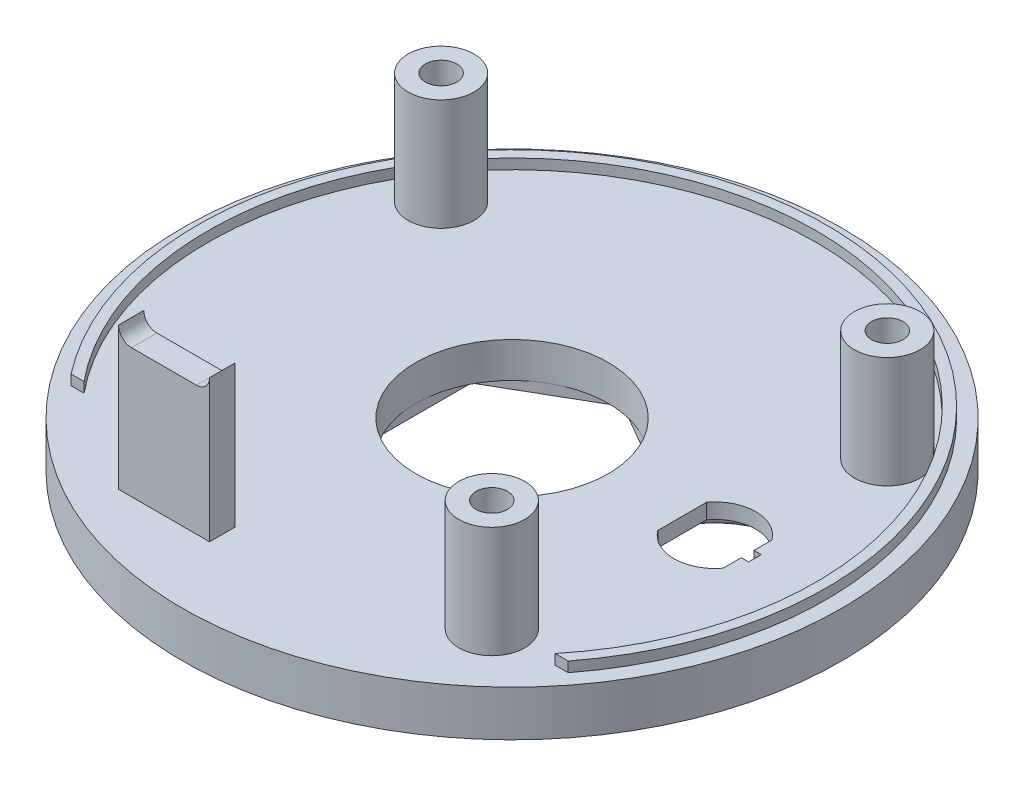
SolidWorks part; units mm, degrees
ref_plane "Front Plane" through (0, 0, 0) normal (0, 0, 1) x (1, 0, 0)
ref_plane "Top Plane" through (0, 0, 0) normal (0, 1, 0) x (1, 0, 0)
ref_plane "Right Plane" through (0, 0, 0) normal (1, 0, 0) x (0, 0, -1)
sketch "Sketch1" plane through (0, 0, 0) normal (0, 1, 0) x (1, 0, 0)
  circle A0 centre (0, 0) radius 32.5
  dimension "D1" = 65
extrude "Boss-Extrude1" add sketch "Sketch1" along normal blind 21
shell "Shell1" thickness 2.5
sketch "Sketch4" plane through (0, 21, 0) normal (0, 1, 0) x (1, 0, 0)
  line L0 (-19.2835, -22.9814) -> (19.2835, -22.9814)
  line L1 (-19.2835, -22.9814) -> (-22.9805, -22.9814)
  line L2 (19.2835, -22.9814) -> (22.9805, -22.9814)
  circle A0 centre (0, 0) radius 30 construction
  circle A1 centre (0, 0) radius 32.5 construction
  arc A2 (-22.9805, -22.9814) -> (22.9805, -22.9814) centre (0, 0) ccw
  dimension "D1" = 38.567
extrude "Cut-Extrude2" cut sketch "Sketch4" against normal up to surface (18.5 mm away) up to face at (0, 2.5, 30)
sketch "Sketch5" plane through (0, 2.5, 0) normal (0, 1, 0) x (1, 0, 0)
  line L4 (-22.9805, -22.9814) -> (22.9805, -22.9814)
  line L5 (-20.1729, -25.4814) -> (20.1729, -25.4814)
  arc A1 (-22.9805, -22.9814) -> (-20.1729, -25.4814) centre (0, 0) ccw
  arc A2 (-22.9805, -22.9814) -> (22.9805, -22.9814) centre (0, 0) ccw construction
  arc A3 (20.1729, -25.4814) -> (22.9805, -22.9814) centre (0, 0) ccw
  dimension "D1" = 2.5
extrude "Boss-Extrude2" add sketch "Sketch5" along normal through all
sketch "Sketch9" plane through (0, 2.5, 0) normal (0, 1, 0) x (1, 0, 0)
  circle A0 centre (-22, 15) radius 3.25
  circle A1 centre (22, 15) radius 3.25
  circle A2 centre (17, -19) radius 3.25
  dimension "D6" = 6.5
  dimension "D1" = 22
  dimension "D2" = 15
  dimension "D3" = 22
  dimension "D4" = 19
  dimension "D5" = 17
extrude "Boss-Extrude3" add sketch "Sketch9" along normal blind 10.97
sketch "Sketch10" plane through (0, 21, 0) normal (0, 1, 0) x (1, 0, 0)
  line L0 (-20.1729, -25.4814) -> (-13.33, -25.4814)
  line L1 (-20.1729, -25.4814) -> (20.1729, -25.4814) construction
  line L2 (-13.33, -25.4814) -> (-13.33, -22.9814)
  line L3 (19.2835, -22.9814) -> (-19.2835, -22.9814) construction
  line L4 (-13.33, -22.9814) -> (-19.2835, -22.9814)
  line L5 (20.1729, -25.4814) -> (-4.35, -25.4814)
  line L6 (-4.35, -25.4814) -> (-4.35, -22.9814)
  line L7 (-4.35, -22.9814) -> (19.2835, -22.9814)
  arc A0 (-20.1729, -25.4814) -> (20.1729, -25.4814) centre (0, 0) cw
  arc A1 (20.1729, -25.4814) -> (-20.1729, -25.4814) centre (0, 0) ccw construction
  arc A2 (-19.2835, -22.9814) -> (19.2835, -22.9814) centre (0, 0) cw
  arc A3 (19.2835, -22.9814) -> (-19.2835, -22.9814) centre (0, 0) ccw construction
  dimension "D1" = 8.98
  dimension "D2" = 5.9535
extrude "Cut-Extrude4" cut sketch "Sketch10" against normal up to surface (18.5 mm away)
sketch "Sketch11" plane through (0, 0, 25.4814) normal (0, 0, 1) x (1, 0, 0)
  line L0 (-12.04, 16.52) -> (-5.64, 16.52) construction
  line L1 (-13.33, 21) -> (-4.35, 21) construction
  line L3 (-12.04, 15.23) -> (-5.64, 15.23)
  line L4 (-13.33, 2.5) -> (-4.35, 2.5) construction
  line L5 (-4.35, 2.5) -> (-4.35, 21) construction
  line L7 (-13.33, 16.52) -> (-13.33, 21)
  line L8 (-13.33, 21) -> (-4.35, 21)
  line L9 (-4.35, 16.52) -> (-4.35, 21)
  line L10 (-13.33, 2.5) -> (-13.33, 21) construction
  arc A0 (-13.33, 16.52) -> (-12.04, 15.23) centre (-12.04, 16.52) ccw
  arc A1 (-5.64, 15.23) -> (-4.35, 16.52) centre (-5.64, 16.52) ccw
  point P4 (-8.84, 14.2241)
  dimension "D1" = 1.29
  dimension "D2" = 12.73
extrude "Cut-Extrude5" cut sketch "Sketch11" against normal through all
sketch "Sketch12" plane through (0, 2.5, 0) normal (0, 1, 0) x (1, 0, 0)
  line L0 (-24.5093, -18.9814) -> (-23.2315, -18.9814)
  line L1 (23.2315, -18.9814) -> (24.5093, -18.9814)
  line L2 (-4.35, -22.9814) -> (-13.33, -22.9814) construction
  arc A0 (-23.2315, -18.9814) -> (23.2315, -18.9814) centre (0, 0) cw
  arc A1 (-24.5093, -18.9814) -> (24.5093, -18.9814) centre (0, 0) cw
  dimension "D1" = 1
  dimension "D3" = 31
  dimension "D2" = 4
extrude "Boss-Extrude4" add sketch "Sketch12" along normal blind 1
sketch "Sketch15" plane through (0, 0, 0) normal (0, -1, 0) x (1, 0, 0)
  circle A0 centre (0, 0) radius 32.5
  circle A1 centre (0, 0) radius 32.5 construction
extrude "Boss-Extrude5" add sketch "Sketch15" along normal blind 2
sketch "Sketch13" plane through (0, 2.5, 0) normal (0, 1, 0) x (1, 0, 0)
  line L0 (16.775, 2.4083) -> (16.775, -2.4083)
  line L3 (23.225, 2.4083) -> (23.225, 0.625)
  line L4 (23.225, -0.625) -> (23.225, -2.4083)
  line L5 (23.225, 0.625) -> (23.95, 0.625)
  line L7 (23.225, -0.625) -> (23.95, -0.625)
  line L8 (23.95, 0.625) -> (23.95, -0.625)
  line L9 (16.775, 2.4083) -> (23.225, 2.4083) construction
  line L10 (16.775, -2.4083) -> (23.225, -2.4083) construction
  arc A2 (16.775, -2.4083) -> (23.225, -2.4083) centre (20, 0) ccw
  arc A3 (23.225, 2.4083) -> (16.775, 2.4083) centre (20, 0) ccw
  circle A4 centre (0, 0) radius 9.5
  point P12 (23.95, 0)
  dimension "D1" = 8.05
  dimension "D4" = 19
  dimension "D2" = 20
  dimension "D3" = 6.45
  dimension "D5" = 3.95
  dimension "D6" = 1.25
extrude "Cut-Extrude6" cut sketch "Sketch13" against normal through all
sketch "Sketch17" plane through (0, -2, 0) normal (0, -1, 0) x (1, 0, 0)
  line L1 (9.5, -5.4848) -> (9.5, 5.4848)
  line L2 (9.5, 5.4848) -> (0, 10.9697)
  line L3 (0, 10.9697) -> (-9.5, 5.4848)
  line L4 (-9.5, 5.4848) -> (-9.5, -5.4848)
  line L5 (-9.5, -5.4848) -> (0, -10.9697)
  line L6 (0, -10.9697) -> (9.5, -5.4848)
  circle A0 centre (0, 0) radius 9.5 construction
  circle A1 centre (0, 0) radius 9.5 construction
extrude "Cut-Extrude7" cut sketch "Sketch17" against normal blind 1
sketch "Sketch18" plane through (0, -2, 0) normal (0, -1, 0) x (1, 0, 0)
  circle A0 centre (20, 0) radius 7.5
  dimension "D1" = 15
extrude "Cut-Extrude8" cut sketch "Sketch18" against normal offset from surface (3 mm away) 1.5
sketch "Sketch21" plane through (0, -2, 0) normal (0, -1, 0) x (1, 0, 0)
  circle A0 centre (-22, -15) radius 3
  circle A1 centre (22, -15) radius 3
  circle A2 centre (17, 19) radius 3
  circle A3 centre (17, 19) radius 3.25 construction
  circle A4 centre (22, -15) radius 3.25 construction
  circle A5 centre (-22, -15) radius 3.25 construction
  dimension "D1" = 6
extrude "Cut-Extrude9" cut sketch "Sketch21" against normal blind 3
fillet "Fillet1" radius 0.5 4 edges at (20, -2, -7.5) (17, -2, 16) (22, -2, -18) (-22, -2, -18)
sketch "Sketch23" plane through (0, 1, 0) normal (0, -1, 0) x (1, 0, 0)
  circle A0 centre (-22, -15) radius 1.55
  circle A1 centre (17, 19) radius 1.55
  circle A2 centre (22, -15) radius 1.55
  dimension "D1" = 3.1
extrude "Cut-Extrude10" cut sketch "Sketch23" against normal through all
